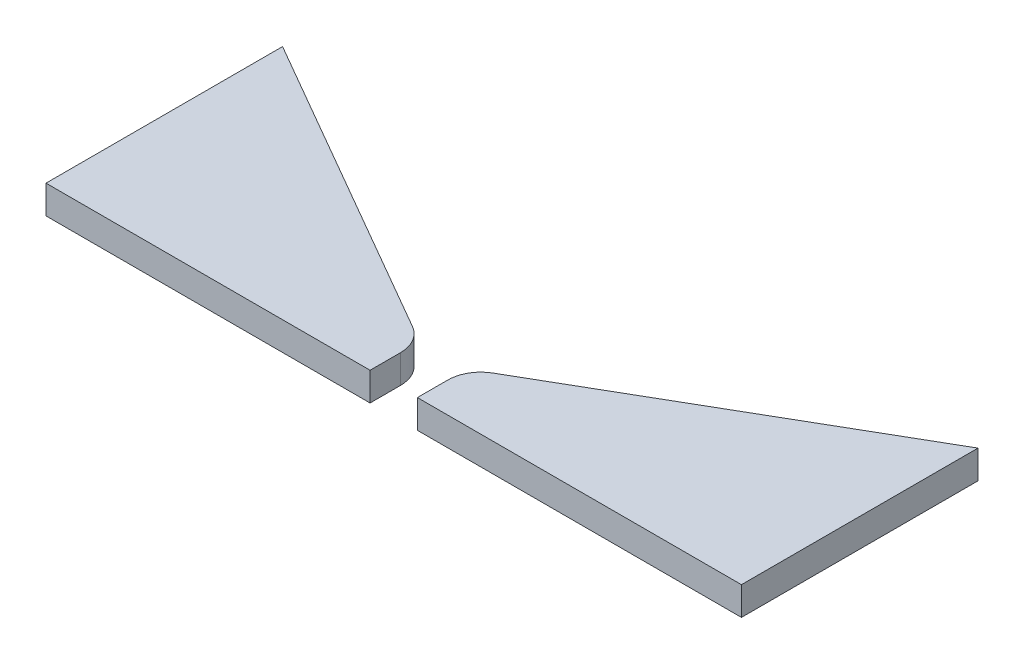
SolidWorks part; units mm, degrees
material "Pine"
ref_plane "Front Plane" through (0, 0, 0) normal (0, 0, 1) x (1, 0, 0)
ref_plane "Top Plane" through (0, 0, 0) normal (0, 1, 0) x (1, 0, 0)
ref_plane "Right Plane" through (0, 0, 0) normal (1, 0, 0) x (0, 0, -1)
sketch "Sketch1" plane through (0, 0, 0) normal (0, 1, 0) x (1, 0, 0)
  line L1 (-233.3625, 0) -> (233.3625, 0) construction
  line L2 (-233.3625, 0) -> (-233.3625, 158.75)
  line L4 (233.3625, 0) -> (233.3625, 158.75)
  line L6 (0, 0) -> (0, 39.5993) construction
  line L7 (-26.9875, 39.5993) -> (-233.3625, 158.75)
  line L8 (233.3625, 158.75) -> (26.9875, 39.5993)
  line L9 (-15.875, 20.3519) -> (-15.875, 0)
  line L10 (15.875, 20.3519) -> (15.875, 0)
  line L11 (-233.3625, 0) -> (-15.875, 0)
  line L12 (15.875, 0) -> (233.3625, 0)
  arc A1 (-26.9875, 39.5993) -> (-15.875, 20.3519) centre (-38.1, 20.3519) cw
  arc A2 (26.9875, 39.5993) -> (15.875, 20.3519) centre (38.1, 20.3519) ccw
  point P4 (0, 0)
  dimension "D5" = 22.225
  dimension "D1" = 466.725
  dimension "D2" = 158.75
  dimension "D3" = 60
  dimension "D4" = 31.75
extrude "Boss-Extrude1" add sketch "Sketch1" along normal blind 19.05 contours A1 L7 L2 L11 L9 | L8 A2 L10 L12 L4
hole_wizard "1/8 (0.125) Diameter Hole1" positions "Sketch2" profile "Sketch3" hole size "1/8" standard "ANSI Inch"
sketch "Sketch2" plane through (0, 0, 0) normal (0, -1, 0) x (-1, 0, 0)
  line L0 (-207.9625, 101.6) -> (-207.9625, 25.4) construction
  line L1 (-207.9625, 25.4) -> (-68.2625, 25.4) construction
  line L3 (-233.3625, 0) -> (-233.3625, 158.75) construction
  line L4 (-15.875, 0) -> (-233.3625, 0) construction
  line L5 (0, 0) -> (0, 158.75) construction
  line L6 (0, 158.75) -> (-233.3625, 158.75) construction
  point P0 (-207.9625, 101.6)
  point P2 (-207.9625, 25.4)
  point P4 (-68.2625, 25.4)
  point P26 (0, 0)
  point P27 (68.2625, 25.4)
  point P28 (207.9625, 25.4)
  point P29 (207.9625, 101.6)
  dimension "D1" = 25.4
  dimension "D2" = 25.4
  dimension "D3" = 76.2
  dimension "D4" = 139.7
sketch "Sketch3" plane through (207.9625, 0, -101.6) normal (1, 0, 0) x (0, 0, -1)
  line L0 (0, 0) -> (0, 12.0664)
  line L1 (0, 12.0664) -> (1.5875, 11.1125)
  line L2 (1.5875, 11.1125) -> (1.5875, 0)
  line L5 (1.5875, 0) -> (0, 0)
  line L10 (0, 12.0664) -> (-1.5875, 11.1125) construction
  line L11 (0, -6.35) -> (0, 107.95) construction
  dimension "Hole Dia." = 3.175
  dimension "Hole Depth" = 11.1125
  dimension "Drill Angle" = 118
